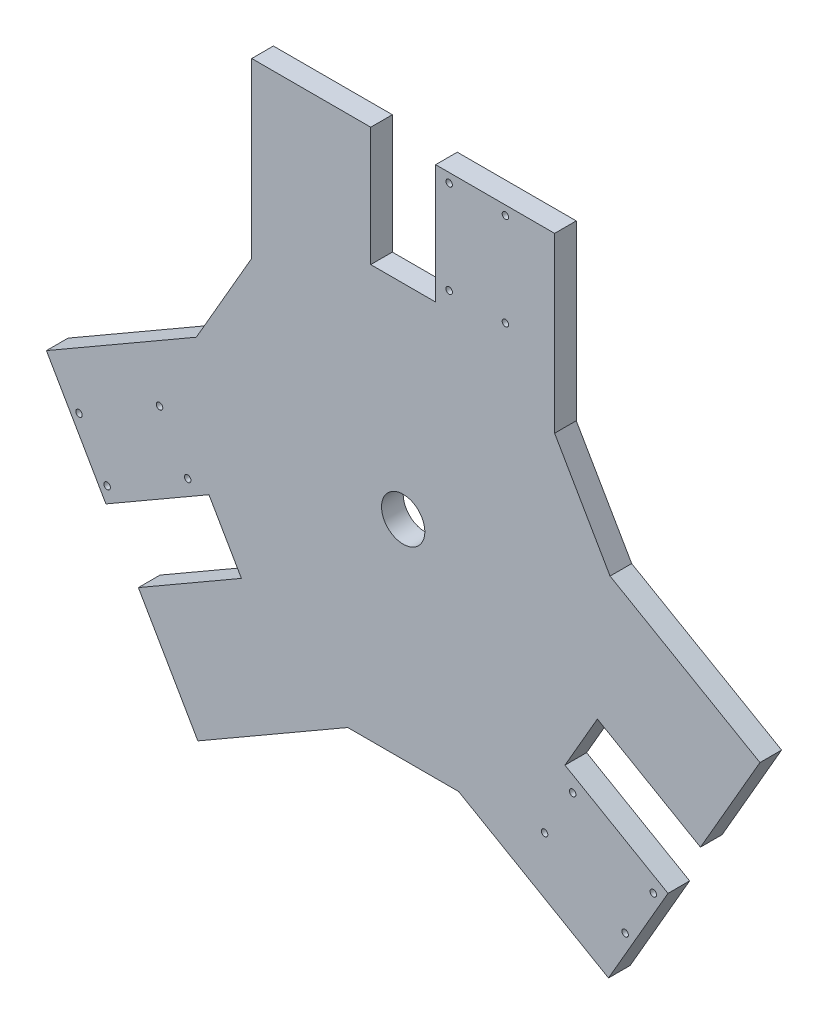
SolidWorks part; units mm, degrees
ref_plane "Plan de face" through (0, 0, 0) normal (0, 0, 1) x (1, 0, 0)
ref_plane "Plan de dessus" through (0, 0, 0) normal (0, 1, 0) x (1, 0, 0)
ref_plane "Plan de droite" through (0, 0, 0) normal (1, 0, 0) x (0, 0, -1)
sketch "Esquisse1" plane through (0, 0, 0) normal (0, 0, 1) x (1, 0, 0)
  line L0 (0, 48.8854) -> (0, -101.1146) construction
  line L1 (-70, 48.8854) -> (70, 48.8854)
  line L2 (-70, 48.8854) -> (-70, -31.1146)
  line L3 (0, -101.1146) -> (-129.9038, -176.1146) construction
  line L4 (-164.9038, -115.4928) -> (-94.9038, -236.7364)
  line L5 (-164.9038, -115.4928) -> (-95.6218, -75.4928)
  line L6 (94.9038, -236.7364) -> (25.6218, -196.7364)
  line L7 (-94.9038, -236.7364) -> (-25.6218, -196.7364)
  line L8 (70, 48.8854) -> (70, -31.1146)
  line L9 (0, -101.1146) -> (129.9038, -176.1146) construction
  line L10 (129.9038, -176.1146) -> (94.9038, -236.7364)
  line L11 (94.9038, -236.7364) -> (164.9038, -115.4928)
  line L12 (164.9038, -115.4928) -> (95.6218, -75.4928)
  line L13 (25.6218, -196.7364) -> (-25.6218, -196.7364)
  line L14 (95.6218, -75.4928) -> (70, -31.1146)
  line L15 (-95.6218, -75.4928) -> (-70, -31.1146)
  dimension "D1" = 120
  dimension "D2" = 120
extrude "Boss.-Extru.1" add sketch "Esquisse1" along normal blind 10 contours L6 L13 L7 L4 L5 L15 L2 L1 L8 L14 L12 L11
sketch "Esquisse2" plane through (0, 0, 0) normal (0, 0, -1) x (-1, 0, 0)
  circle A0 centre (0, -100.5413) radius 10
extrude "Enlèv. mat.-Extru.1" cut sketch "Esquisse2" against normal through all
sketch "Esquisse3" plane through (0, 0, 10) normal (0, 0, 1) x (1, 0, 0)
  line L0 (-88.6987, -233.1539) -> (-116.1987, -185.5225) construction
  line L1 (-94.9038, -236.7364) -> (-25.6218, -196.7364) construction
  line L2 (-88.6987, -233.1539) -> (-94.9038, -236.7364) construction
  line L4 (-94.9038, -236.7364) -> (-164.2002, -116.7116) construction
  line L5 (-164.9038, -115.4928) -> (-94.9038, -236.7364) construction
  line L6 (-164.2002, -116.7116) -> (-158.6987, -111.9103) construction
  line L7 (-164.9038, -115.4928) -> (-95.6218, -75.4928) construction
  line L8 (-158.6987, -111.9103) -> (-131.1987, -159.5417) construction
  line L9 (-89.7724, -135.6242) -> (-137.4038, -163.1242)
  line L10 (-137.4038, -163.1242) -> (-122.4038, -189.105)
  line L11 (-89.7724, -135.6242) -> (-74.7724, -161.605)
  line L12 (-74.7724, -161.605) -> (-122.4038, -189.105)
extrude "Enlèv. mat.-Extru.2" cut sketch "Esquisse3" against normal through all
sketch "Esquisse4" plane through (0, 0, 10) normal (0, 0, 1) x (1, 0, 0)
  line L0 (94.9038, -236.7364) -> (122.4038, -189.105) construction
  line L1 (94.9038, -236.7364) -> (164.9038, -115.4928) construction
  line L2 (164.9038, -115.4928) -> (137.4038, -163.1242) construction
  line L3 (137.4038, -163.1242) -> (122.4038, -189.105)
  line L4 (122.4038, -189.105) -> (74.7724, -161.605)
  line L5 (74.7724, -161.605) -> (89.7724, -135.6242)
  line L6 (89.7724, -135.6242) -> (137.4038, -163.1242)
extrude "Enlèv. mat.-Extru.3" cut sketch "Esquisse4" against normal through all
sketch "Esquisse5" plane through (0, 0, 10) normal (0, 0, 1) x (1, 0, 0)
  line L0 (70, 48.8854) -> (15, 48.8854) construction
  line L1 (-70, 48.8854) -> (70, 48.8854) construction
  line L2 (-70, 48.8854) -> (-15, 48.8854) construction
  line L3 (-15, 48.8854) -> (15, 48.8854)
  line L4 (15, 48.8854) -> (15, -6.1146)
  line L5 (15, -6.1146) -> (-15, -6.1146)
  line L6 (-15, -6.1146) -> (-15, 48.8854)
extrude "Enlèv. mat.-Extru.4" cut sketch "Esquisse5" against normal through all
sketch "Esquisse6" plane through (0, 0, 10) normal (0, 0, 1) x (1, 0, 0)
  line L0 (-164.9038, -115.4928) -> (-137.4038, -163.1242) construction
  line L1 (-89.7724, -135.6242) -> (-137.4038, -163.1242) construction
  line L2 (-89.7724, -135.6242) -> (-137.4038, -163.1242) construction
  circle A0 centre (-136.8482, -155.5866) radius 1.5
  circle A1 centre (-99.6091, -134.0866) radius 1.5
  circle A2 centre (-149.8482, -133.0699) radius 1.5
  circle A3 centre (-112.6091, -111.5699) radius 1.5
  dimension "D1" = 4.25
  dimension "D2" = 6.25
  dimension "D3" = 6.25
  dimension "D4" = 43
  dimension "D5" = 4.25
  dimension "D6" = 26
  dimension "D7" = 26
  dimension "D8" = 43
extrude "Enlèv. mat.-Extru.5" cut sketch "Esquisse6" against normal blind 10
sketch "Esquisse7" plane through (0, 0, 10) normal (0, 0, 1) x (1, 0, 0)
  line L0 (15, -6.1146) -> (15, 48.8854) construction
  line L1 (15, 48.8854) -> (70, 48.8854) construction
  line L2 (94.9038, -236.7364) -> (122.4038, -189.105) construction
  line L3 (74.7724, -161.605) -> (122.4038, -189.105) construction
  circle A0 centre (21.25, 44.6354) radius 1.5
  circle A1 centre (47.25, 44.6354) radius 1.5
  circle A2 centre (21.25, 1.6354) radius 1.5
  circle A3 centre (47.25, 1.6354) radius 1.5
  circle A4 centre (115.5982, -192.3926) radius 1.5
  circle A5 centre (78.3591, -170.8926) radius 1.5
  circle A6 centre (65.3591, -193.4093) radius 1.5
  circle A7 centre (102.5982, -214.9093) radius 1.5
  dimension "D1" = 6.25
  dimension "D2" = 4.25
  dimension "D3" = 4.25
  dimension "D4" = 26
  dimension "D5" = 43
  dimension "D6" = 6.25
  dimension "D7" = 4.25
  dimension "D8" = 6.25
  dimension "D9" = 6.25
  dimension "D10" = 43
  dimension "D11" = 4.25
  dimension "D12" = 26
  dimension "D13" = 26
  dimension "D14" = 43
  dimension "D15" = 26
extrude "Enlèv. mat.-Extru.6" cut sketch "Esquisse7" against normal blind 60
